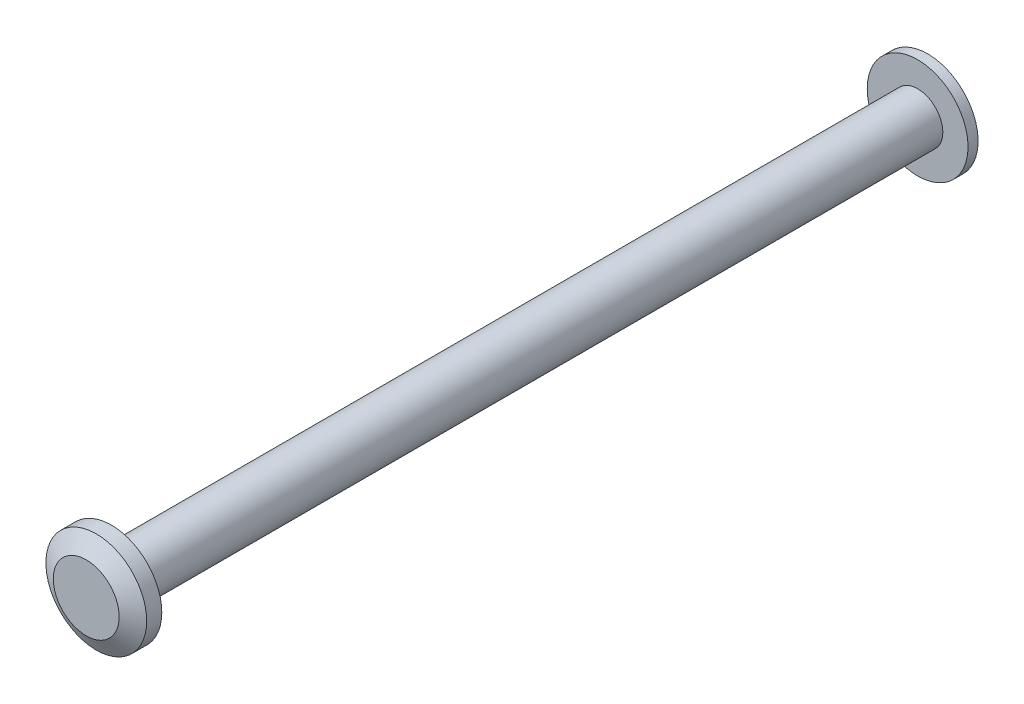
SolidWorks part; units mm, degrees
ref_plane "Front Plane" through (0, 0, 0) normal (0, 0, 1) x (1, 0, 0)
ref_plane "Top Plane" through (0, 0, 0) normal (0, 1, 0) x (1, 0, 0)
ref_plane "Right Plane" through (0, 0, 0) normal (1, 0, 0) x (0, 0, -1)
sketch "Sketch1" plane through (0, 0, 0) normal (0, 0, 1) x (1, 0, 0)
  circle A0 centre (0, 0) radius 0.5
  dimension "D1" = 1
extrude "Boss-Extrude1" add sketch "Sketch1" along normal blind 16
sketch "Sketch2" plane through (0, 0, 0) normal (0, 0, -1) x (-1, 0, 0)
  circle A0 centre (0, 0) radius 1
extrude "Boss-Extrude2" add sketch "Sketch2" along normal blind 0.4
chamfer "Chamfer1" distance 0.2 angle 60 1 edges at (-1, 0, -0.4)
sketch "Sketch3" plane through (0, 0, 16) normal (0, 0, 1) x (1, 0, 0)
  circle A0 centre (0, 0) radius 1
extrude "Boss-Extrude3" add sketch "Sketch3" along normal blind 0.5
chamfer "Chamfer2" distance 0.2 angle 60 1 edges at (1, 0, 16.5)
